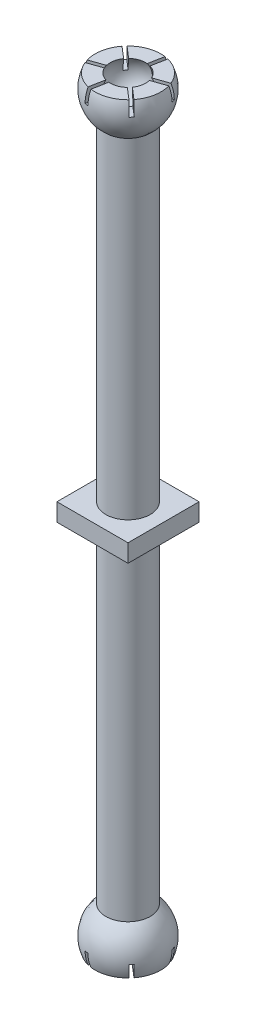
SolidWorks part; units mm, degrees
ref_plane "Alzado" through (0, 0, 0) normal (0, 0, 1) x (1, 0, 0)
ref_plane "Planta" through (0, 0, 0) normal (0, 1, 0) x (1, 0, 0)
ref_plane "Vista lateral" through (0, 0, 0) normal (1, 0, 0) x (0, 0, -1)
sketch "Croquis1" plane through (0, 0, 0) normal (0, 1, 0) x (1, 0, 0)
  circle A0 centre (0, 0) radius 25
  dimension "D1" = 50
extrude "Saliente-Extruir1" add sketch "Croquis1" along normal mid plane 826
ref_plane "Plano1" through (0, -413, 0) normal (0, -1, 0) x (-1, 0, 0)
ref_plane "Plano2" through (0, 413, 0) normal (0, 1, 0) x (1, 0, 0)
sketch "Croquis2" plane through (0, -413, 0) normal (0, -1, 0) x (1, 0, 0)
  line L0 (0, 40) -> (0, -40)
  line L1 (0, 0) -> (0, 49.8461) construction
  arc A1 (0, 40) -> (0, -40) centre (0, 0) ccw
  dimension "D1" = 40
revolve "Revolución1" add sketch "Croquis2" angle 360 about L1
sketch "Croquis3" plane through (0, 413, 0) normal (0, 1, 0) x (1, 0, 0)
  line L0 (0, 0) -> (0, 40) construction
  line L1 (0, 40) -> (0, -40)
  circle A0 centre (0, 0) radius 40 construction
  arc A1 (0, 40) -> (0, -40) centre (0, 0) ccw
revolve "Revolución2" add sketch "Croquis3" angle 360 about L0
ref_plane "Plano3" through (0, -428, 0) normal (0, -1, 0) x (-1, 0, 0)
ref_plane "Plano4" through (0, 428, 0) normal (0, 1, 0) x (1, 0, 0)
sketch "Croquis4" plane through (0, -428, 0) normal (0, -1, 0) x (-1, 0, 0)
  circle A0 centre (0, 0) radius 68.5789
extrude "Cortar-Extruir1" cut sketch "Croquis4" along normal through all
sketch "Croquis5" plane through (0, 428, 0) normal (0, 1, 0) x (1, 0, 0)
  circle A0 centre (0, 0) radius 66.2808
extrude "Cortar-Extruir3" cut sketch "Croquis5" along normal through all
sketch "Croquis8" plane through (0, -413, 0) normal (0, -1, 0) x (-1, 0, 0)
  line L0 (0, -25) -> (0, 25)
  line L1 (0, 0) -> (0, 25) construction
  line L2 (0, -25) -> (0, 25)
  arc A0 (0, -25) -> (0, 25) centre (0, 0) cw
  dimension "D1" = 25
revolve "Cortar-Revolución1" cut sketch "Croquis8" angle 360 about L1
sketch "Croquis9" plane through (0, -413, 0) normal (0, -1, 0) x (1, 0, 0)
  line L11 (2.6095, -3.0316) -> (39.4118, -15.9048)
  line L12 (1.3207, 3.7757) -> (30.8703, 29.2108)
  line L14 (-3.9302, -0.7441) -> (-40.7325, 12.1291)
  line L15 (-1.3207, -3.7757) -> (-30.8703, -29.2108)
  line L16 (2.6095, -3.0316) -> (9.8622, -41.3399)
  line L36 (-2.6095, 3.0316) -> (-39.4118, 15.9048)
  line L37 (-1.3207, -3.7757) -> (5.932, -42.084)
  line L39 (-3.9302, -0.7441) -> (-33.4798, -26.1792)
  line L41 (-2.6095, 3.0316) -> (-9.8622, 41.3399)
  line L43 (1.3207, 3.7757) -> (-5.932, 42.084)
  line L44 (3.9302, 0.7441) -> (40.7325, -12.1291)
  line L45 (3.9302, 0.7441) -> (33.4798, 26.1792)
  arc A0 (33.4798, 26.1792) -> (30.8703, 29.2108) centre (0, 0) ccw
  arc A1 (-5.932, 42.084) -> (-9.8622, 41.3399) centre (0, 0) ccw
  arc A2 (-39.4118, 15.9048) -> (-40.7325, 12.1291) centre (0, 0) ccw
  arc A3 (-33.4798, -26.1792) -> (-30.8703, -29.2108) centre (0, 0) ccw
  arc A4 (5.932, -42.084) -> (9.8622, -41.3399) centre (0, 0) ccw
  arc A5 (39.4118, -15.9048) -> (40.7325, -12.1291) centre (0, 0) ccw
  point P4 (0, 0)
  point P12 (0, 0)
  dimension "D4" = 85
extrude "Cortar-Extruir5" cut sketch "Croquis9" along normal through all
mirror "Simetría1" about plane through (0, 0, 0) normal (0, 1, 0) of "Cortar-Extruir5", "Cortar-Revolución1"
sketch "Croquis10" plane through (0, 0, 0) normal (0, 1, 0) x (1, 0, 0)
  line L1 (-40, 40) -> (40, 40)
  line L2 (-40, 40) -> (-40, -40)
  line L3 (-40, -40) -> (40, -40)
  line L4 (40, 40) -> (40, -40)
  line L5 (-40, 40) -> (40, -40) construction
  line L6 (-40, -40) -> (40, 40) construction
  point P0 (0, 0)
  dimension "D1" = 80
extrude "Saliente-Extruir2" add sketch "Croquis10" along normal mid plane 20
